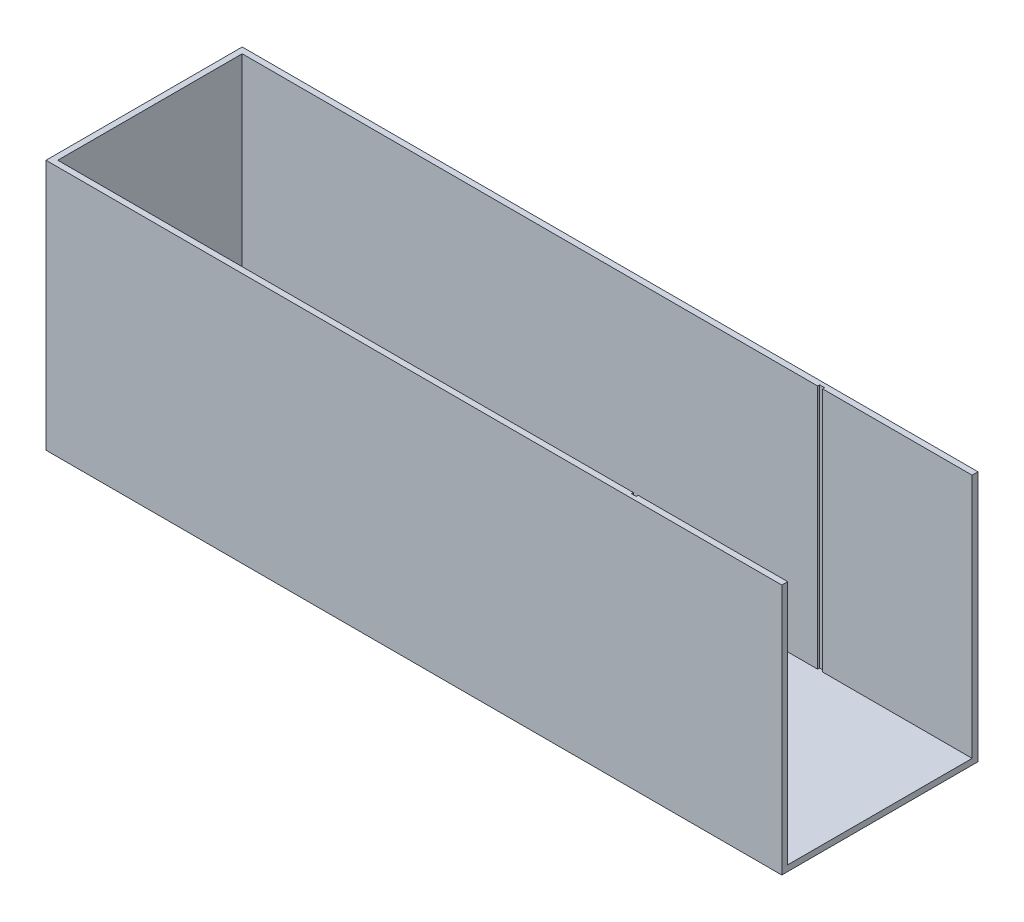
SolidWorks part; units mm, degrees
ref_plane "Front Plane" through (0, 0, 0) normal (0, 0, 1) x (1, 0, 0)
ref_plane "Top Plane" through (0, 0, 0) normal (0, 1, 0) x (1, 0, 0)
ref_plane "Right Plane" through (0, 0, 0) normal (1, 0, 0) x (0, 0, -1)
sketch "Sketch1" plane through (0, 0, 0) normal (0, 1, 0) x (1, 0, 0)
  line L1 (-750, -200) -> (750, -200)
  line L2 (-750, -200) -> (-750, 200)
  line L3 (-750, 200) -> (750, 200)
  line L4 (750, -200) -> (750, 200)
  line L5 (-750, -200) -> (750, 200) construction
  line L6 (-750, 200) -> (750, -200) construction
  point P0 (0, 0)
  dimension "D1" = 1500
  dimension "D2" = 400
extrude "Boss-Extrude1" add sketch "Sketch1" along normal mid plane 12
sketch "Sketch2" plane through (0, 6, 0) normal (0, 1, 0) x (1, 0, 0)
  line L8 (738, 188) -> (750, 188)
  line L9 (750, -200) -> (750, 200) construction
  line L10 (750, 188) -> (750, 200)
  line L11 (738, -188) -> (750, -188)
  line L12 (750, -188) -> (750, -200)
  line L22 (750, -200) -> (750, 200)
  line L23 (-750, -200) -> (750, -200)
  line L24 (-750, 200) -> (-750, -200)
  line L25 (750, 200) -> (-750, 200)
  line L27 (-750, -200) -> (750, -200)
  line L28 (-750, 200) -> (-750, -200)
  line L29 (750, 200) -> (-750, 200)
  line L30 (738, 188) -> (-738, 188)
  line L31 (-738, 188) -> (-738, -188)
  line L32 (-738, -188) -> (738, -188)
  line L38 (738, -188) -> (738, 188) construction
  line L39 (750, -200) -> (750, 200) construction
  dimension "D1" = 0
  dimension "D2" = 12
extrude "Boss-Extrude2" add sketch "Sketch2" along normal blind 500
sketch "Sketch3" plane through (0, 0, -188) normal (0, 0, 1) x (1, 0, 0)
  line L0 (-750, 506) -> (750, 506) construction
  line L1 (435.2, 506) -> (445.2, 506)
  line L2 (435.2, 506) -> (435.2, 6)
  line L3 (435.2, 6) -> (445.2, 6)
  line L4 (445.2, 506) -> (445.2, 6)
  line L5 (750, 6) -> (-738, 6) construction
  line L6 (750, 506) -> (750, -6) construction
  dimension "D1" = 10
  dimension "D2" = 304.8
extrude "Cut-Extrude1" cut sketch "Sketch3" against normal blind 4
mirror "Mirror1" about plane through (0, 0, 0) normal (0, 0, 1) of "Cut-Extrude1"
